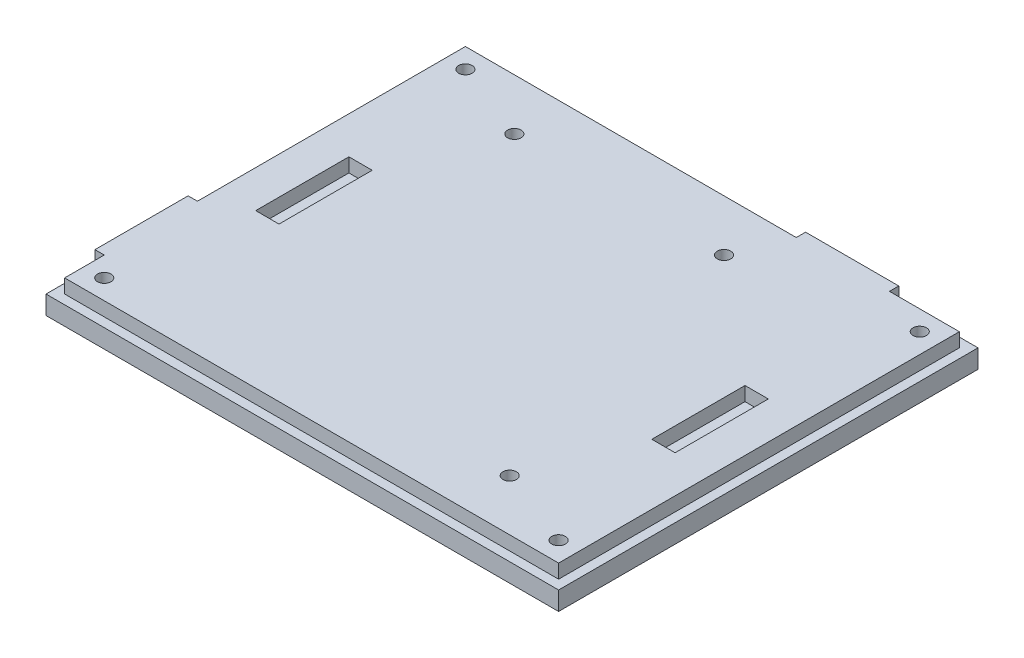
SolidWorks part; units mm, degrees
ref_plane "Front Plane" through (0, 0, 0) normal (0, 0, 1) x (1, 0, 0)
ref_plane "Top Plane" through (0, 0, 0) normal (0, 1, 0) x (1, 0, 0)
ref_plane "Right Plane" through (0, 0, 0) normal (1, 0, 0) x (0, 0, -1)
sketch "Sketch1" plane through (0, 0, 0) normal (0, 1, 0) x (1, 0, 0)
  line L1 (-55, 45) -> (55, 45)
  line L2 (-55, 45) -> (-55, -45)
  line L3 (-55, -45) -> (55, -45)
  line L4 (55, 45) -> (55, -45)
extrude "Boss-Extrude1" add sketch "Sketch1" along normal blind 7
hole_wizard "M2.5 Clearance Hole1" positions "Sketch2" profile "Sketch3" hole size "M2.5" standard "ANSI Metric"
sketch "Sketch2" plane through (0, 7, 0) normal (0, 1, 0) x (1, 0, 0)
  point P0 (-31.5, 32)
  point P2 (13.5, 32)
  point P4 (31.5, -32)
sketch "Sketch3" plane through (-31.5, 7, -32) normal (1, 0, 0) x (0, 0, 1)
  line L0 (0, 0) -> (0, 5.8712)
  line L1 (0, 5.8712) -> (1.45, 5)
  line L2 (1.45, 5) -> (1.45, 0)
  line L5 (1.45, 0) -> (0, 0)
  line L10 (0, 5.8712) -> (-1.45, 5) construction
  line L11 (0, -6.35) -> (0, 107.95) construction
  dimension "Hole Dia." = 2.9
  dimension "Hole Depth" = 5
  dimension "Drill Angle" = 118
sketch "Sketch8" plane through (0, 7, 0) normal (0, 1, 0) x (1, 0, 0)
  line L1 (-45, 10) -> (-40, 10)
  line L2 (-45, 10) -> (-45, -10)
  line L3 (-45, -10) -> (-40, -10)
  line L4 (-40, 10) -> (-40, -10)
  line L5 (45, 10) -> (40, 10)
  line L6 (45, 10) -> (45, -10)
  line L7 (45, -10) -> (40, -10)
  line L8 (40, 10) -> (40, -10)
extrude "Cut-Extrude5" cut sketch "Sketch8" against normal blind 3
sketch "Sketch10" plane through (0, 7, 0) normal (0, 1, 0) x (1, 0, 0)
  line L1 (-55, 45) -> (-53, 45)
  line L2 (-55, 45) -> (-55, -14.5)
  line L3 (-55, -14.5) -> (-53, -14.5)
  line L4 (-53, 45) -> (-53, -14.5)
  line L5 (-55, -45) -> (-53, -45)
  line L6 (-55, -45) -> (-55, -34.5)
  line L7 (-55, -34.5) -> (-53, -34.5)
  line L8 (-53, -45) -> (-53, -34.5)
  point P10 (0, 0)
  point P11 (0, 0)
  point P12 (0, 0)
  point P13 (0, 0)
  point P14 (0, 0)
  point P15 (0, 0)
  point P16 (0, 0)
  point P17 (0, 0)
  point P18 (0, 0)
  point P19 (0, 0)
  point P20 (0, 0)
  point P21 (0, 0)
  point P22 (0, 0)
extrude "Cut-Extrude6" cut sketch "Sketch10" against normal blind 3
sketch "Sketch11" plane through (0, 7, 0) normal (0, 1, 0) x (1, 0, 0)
  line L1 (-53, 45) -> (18, 45)
  line L2 (-53, 45) -> (-53, 43)
  line L3 (-53, 43) -> (18, 43)
  line L4 (18, 45) -> (18, 43)
  line L5 (55, 45) -> (38, 45)
  line L6 (55, 45) -> (55, 43)
  line L7 (55, 43) -> (38, 43)
  line L8 (38, 45) -> (38, 43)
  point P10 (0, 0)
  point P11 (0, 0)
  point P12 (0, 0)
  point P13 (0, 0)
  point P14 (0, 0)
extrude "Cut-Extrude7" cut sketch "Sketch11" against normal blind 3
sketch "Sketch12" plane through (0, 7, 0) normal (0, 1, 0) x (1, 0, 0)
  line L0 (-53, -45) -> (55, -45) construction
  line L1 (55, 43) -> (53, 43)
  line L2 (55, 43) -> (55, -45)
  line L3 (55, -45) -> (53, -45)
  line L4 (53, 43) -> (53, -45)
extrude "Cut-Extrude8" cut sketch "Sketch12" against normal blind 3
sketch "Sketch13" plane through (0, 7, 0) normal (0, 1, 0) x (1, 0, 0)
  line L0 (-53, -45) -> (-53, -34.5) construction
  line L1 (53, -45) -> (-53, -45)
  line L2 (53, -45) -> (53, -43)
  line L3 (53, -43) -> (-53, -43)
  line L4 (-53, -45) -> (-53, -43)
extrude "Cut-Extrude9" cut sketch "Sketch13" against normal blind 3
hole_wizard "M2.5 Clearance Hole2" positions "Sketch14" profile "Sketch15" hole size "M2.5" standard "ANSI Metric" end condition through all
sketch "Sketch14" plane through (0, 7, 0) normal (0, 1, 0) x (1, 0, 0)
  point P0 (48.75, 38.75)
  point P2 (-48.75, 38.75)
  point P4 (48.75, -38.75)
  point P6 (-48.75, -38.75)
  point P9 (0, 0)
  point P10 (0, 0)
  point P11 (0, 0)
  point P12 (0, 0)
  point P13 (0, 0)
  point P14 (0, 0)
  point P15 (0, 0)
  point P16 (0, 0)
sketch "Sketch15" plane through (48.75, 7, -38.75) normal (1, 0, 0) x (0, 0, 1)
  line L0 (0, 0) -> (0, 7)
  line L1 (0, 7) -> (1.45, 7)
  line L2 (1.45, 7) -> (1.45, 0)
  line L5 (1.45, 0) -> (0, 0)
  line L11 (0, -6.35) -> (0, 107.95) construction
  dimension "Thru Hole Dia." = 2.9
  dimension "Thru Hole Depth" = 7
